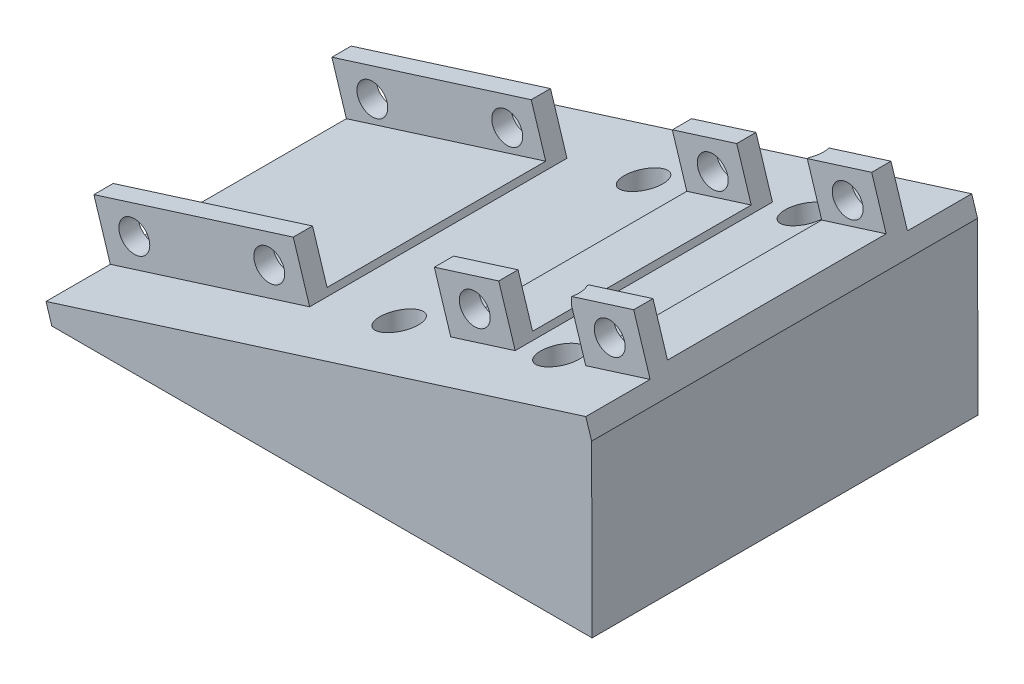
SolidWorks part; units mm, degrees
ref_plane "前视基准面" through (0, 0, 0) normal (0, 0, 1) x (1, 0, 0)
ref_plane "上视基准面" through (0, 0, 0) normal (0, 1, 0) x (1, 0, 0)
ref_plane "右视基准面" through (0, 0, 0) normal (1, 0, 0) x (0, 0, -1)
sketch "草图1" plane through (0, 0, 0) normal (0, 0, 1) x (1, 0, 0)
  line L0 (-38.6831, -5.4708) -> (45.3169, -5.4708)
  line L2 (45.3169, -5.4708) -> (45.244, 20.9913)
  line L4 (-38.6831, -5.4708) -> (-39.5852, -2.6096)
  line L5 (45.244, 20.9913) -> (44.3419, 23.8525)
  line L6 (-39.5852, -2.6096) -> (44.3419, 23.8525)
  dimension "D1" = 84
  dimension "D3" = 88
  dimension "D4" = 3
extrude "凸台-拉伸1" add sketch "草图1" along normal blind 60
sketch "草图2" plane through (-2.831, 8.9789, 0) normal (-0.3007, 0.9537, 0) x (0.9537, 0.3007, 0)
  line L0 (-38.5378, -60) -> (-38.5378, 0) construction
  line L1 (-38.5378, -10) -> (-6.0378, -10)
  line L2 (-38.5378, -10) -> (-38.5378, -13)
  line L3 (-38.5378, -13) -> (-6.0378, -13)
  line L4 (-6.0378, -10) -> (-6.0378, -13)
  line L5 (49.4622, 0) -> (-38.5378, 0) construction
  line L6 (49.4622, -60) -> (-38.5378, -60) construction
  line L7 (-38.5378, -47) -> (-6.0378, -47)
  line L8 (-38.5378, -47) -> (-38.5378, -50)
  line L9 (-38.5378, -50) -> (-6.0378, -50)
  line L10 (-6.0378, -47) -> (-6.0378, -50)
  line L11 (49.4622, -60) -> (49.4622, 0) construction
  line L12 (49.4622, -10) -> (16.9622, -10)
  line L13 (49.4622, -10) -> (49.4622, -13)
  line L14 (49.4622, -13) -> (16.9622, -13)
  line L15 (16.9622, -10) -> (16.9622, -13)
  line L17 (49.4622, -47) -> (16.9622, -47)
  line L18 (49.4622, -47) -> (49.4622, -50)
  line L19 (49.4622, -50) -> (16.9622, -50)
  line L20 (16.9622, -47) -> (16.9622, -50)
  dimension "D1" = 3
  dimension "D2" = 10
  dimension "D3" = 32.5
  dimension "D4" = 3
  dimension "D5" = 10
  dimension "D6" = 32.5
  dimension "D7" = 32.5
  dimension "D8" = 3
  dimension "D9" = 10
extrude "凸台-拉伸2" add sketch "草图2" along normal blind 8.5
sketch "草图3" plane through (-2.831, 8.9789, 0) normal (-0.3007, 0.9537, 0) x (0.9537, 0.3007, 0)
  line L1 (-38.5378, -13) -> (-6.0378, -13)
  line L2 (-38.5378, -13) -> (-38.5378, -47)
  line L3 (-38.5378, -47) -> (-6.0378, -47)
  line L4 (-6.0378, -13) -> (-6.0378, -47)
  line L5 (16.9622, -13) -> (49.4622, -13)
  line L6 (16.9622, -13) -> (16.9622, -47)
  line L7 (16.9622, -47) -> (49.4622, -47)
  line L8 (49.4622, -13) -> (49.4622, -47)
extrude "凸台-拉伸3" add sketch "草图3" along normal blind 1
sketch "草图4" plane through (0, 0, 50) normal (0, 0, 1) x (1, 0, 0)
  line L0 (44.3419, 23.8525) -> (-39.5852, -2.6096) construction
  line L2 (-42.1412, 5.497) -> (-39.5852, -2.6096) construction
  line L4 (-11.1454, 15.2699) -> (-8.5894, 7.1633) construction
  line L5 (10.7901, 22.1861) -> (13.3461, 14.0796) construction
  line L7 (41.7859, 31.9591) -> (44.3419, 23.8525) construction
  circle A0 centre (-35.8502, 3.0033) radius 2.4
  circle A1 centre (-14.8744, 9.6379) radius 2.4
  circle A2 centre (17.0751, 19.7116) radius 2.4
  circle A3 centre (38.0569, 26.3271) radius 2.4
  dimension "D1" = 4.23
  dimension "D2" = 5.25
  dimension "D3" = 4.25
  dimension "D4" = 5.25
  dimension "D5" = 5.25
  dimension "D6" = 4.25
  dimension "D7" = 4.25
  dimension "D8" = 5.25
extrude "切除-拉伸1" cut sketch "草图4" against normal blind 100
sketch "草图6" plane through (0, 0, 10) normal (0, 0, -1) x (-1, 0, 0)
  line L0 (-31.7719, 28.8017) -> (-34.3279, 20.6951)
  line L1 (-41.7859, 31.9591) -> (-10.7901, 22.1861) construction
  line L2 (-44.3419, 23.8525) -> (39.5852, -2.6096) construction
  line L3 (-41.7859, 31.9591) -> (-44.3419, 23.8525) construction
  line L4 (-20.8041, 25.3436) -> (-23.3601, 17.237)
  line L5 (-41.7859, 31.9591) -> (-10.7901, 22.1861) construction
  line L6 (-10.7901, 22.1861) -> (-13.3461, 14.0796) construction
  line L7 (-31.7719, 28.8017) -> (-20.8041, 25.3436)
  line L8 (-34.3279, 20.6951) -> (-23.3601, 17.237)
  point P8 (-43.0639, 27.9058)
  dimension "D1" = 10.5
  dimension "D2" = 10.5
extrude "切除-拉伸3" cut sketch "草图6" against normal blind 100
sketch "草图5" plane through (0, -5.4708, 0) normal (0, -1, 0) x (-1, 0, 0)
  line L1 (38.6831, -60) -> (-45.3169, -60) construction
  line L2 (38.6831, 0) -> (-45.3169, 0) construction
  line L3 (-45.3169, -60) -> (-45.3169, 0) construction
  circle A0 centre (-29.3169, -49) radius 1.62
  circle A1 centre (-29.3169, -11) radius 1.62
  circle A2 centre (-4.3169, -49) radius 1.62
  circle A3 centre (-4.3169, -11) radius 1.62
  dimension "D1" = 3.24
  dimension "D2" = 16
  dimension "D3" = 11
  dimension "D4" = 3.24
  dimension "D5" = 11
  dimension "D7" = 3.24
  dimension "D8" = 11
  dimension "D9" = 25
  dimension "D10" = 3.24
  dimension "D11" = 0
  dimension "D12" = 25
extrude "切除-拉伸4" cut sketch "草图5" against normal blind 100
ref_plane "基准面4" through (0, -2.4708, 0) normal (0, -1, 0) x (-1, 0, 0)
sketch "草图7" plane through (0, -2.4708, 0) normal (0, -1, 0) x (-1, 0, 0)
  circle A0 centre (-29.3169, -11) radius 3
  circle A1 centre (-4.3169, -11) radius 3
  circle A2 centre (-29.3169, -49) radius 3
  circle A3 centre (-4.3169, -49) radius 3
extrude "切除-拉伸5" cut sketch "草图7" against normal blind 100
